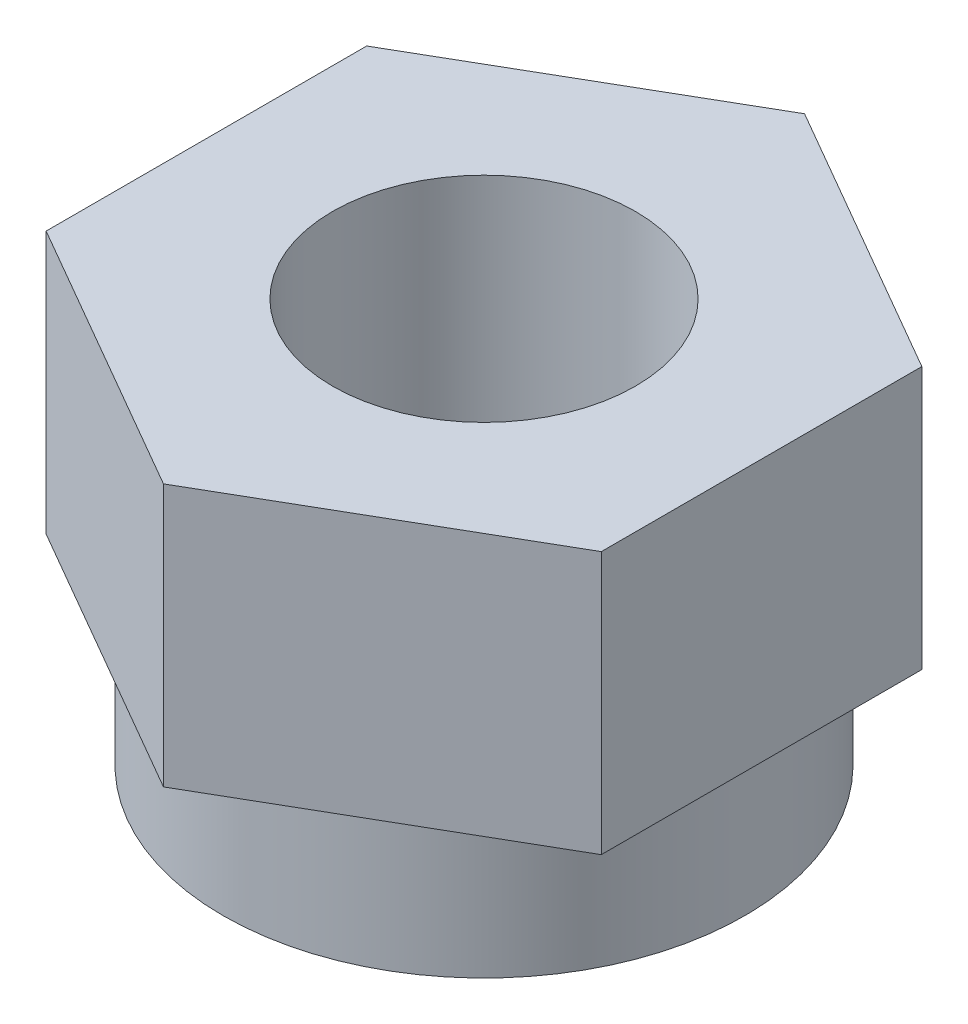
SolidWorks part; units mm, degrees
ref_plane "Front Plane" through (0, 0, 0) normal (0, 0, 1) x (1, 0, 0)
ref_plane "Top Plane" through (0, 0, 0) normal (0, 1, 0) x (1, 0, 0)
ref_plane "Right Plane" through (0, 0, 0) normal (1, 0, 0) x (0, 0, -1)
sketch "Sketch1" plane through (0, 0, 0) normal (0, 1, 0) x (1, 0, 0)
  line L0 (2.75, -1.5877) -> (0, -3.1754)
  line L1 (0, -3.1754) -> (-2.75, -1.5877)
  line L2 (-2.75, -1.5877) -> (-2.75, 1.5877)
  line L3 (-2.75, 1.5877) -> (0, 3.1754)
  line L4 (0, 3.1754) -> (2.75, 1.5877)
  line L5 (2.75, 1.5877) -> (2.75, -1.5877)
extrude "Boss-Extrude1" add sketch "Sketch1" against normal blind 2.6
ref_plane "Plane1" through (0, -2.6, 0) normal (0, 1, 0) x (1, 0, 0)
sketch "Sketch2" plane through (0, -2.6, 0) normal (0, 1, 0) x (1, 0, 0)
  circle A0 centre (0, 0) radius 2.585
extrude "Boss-Extrude2" add sketch "Sketch2" against normal blind 1.4
sketch "Sketch3" plane through (0, 0, 0) normal (0, 1, 0) x (1, 0, 0)
  circle A0 centre (0, 0) radius 1.5
extrude "Cut-Extrude1" cut sketch "Sketch3" against normal through all and the other way through all
cosmetic thread "Cosmetic Thread1"
